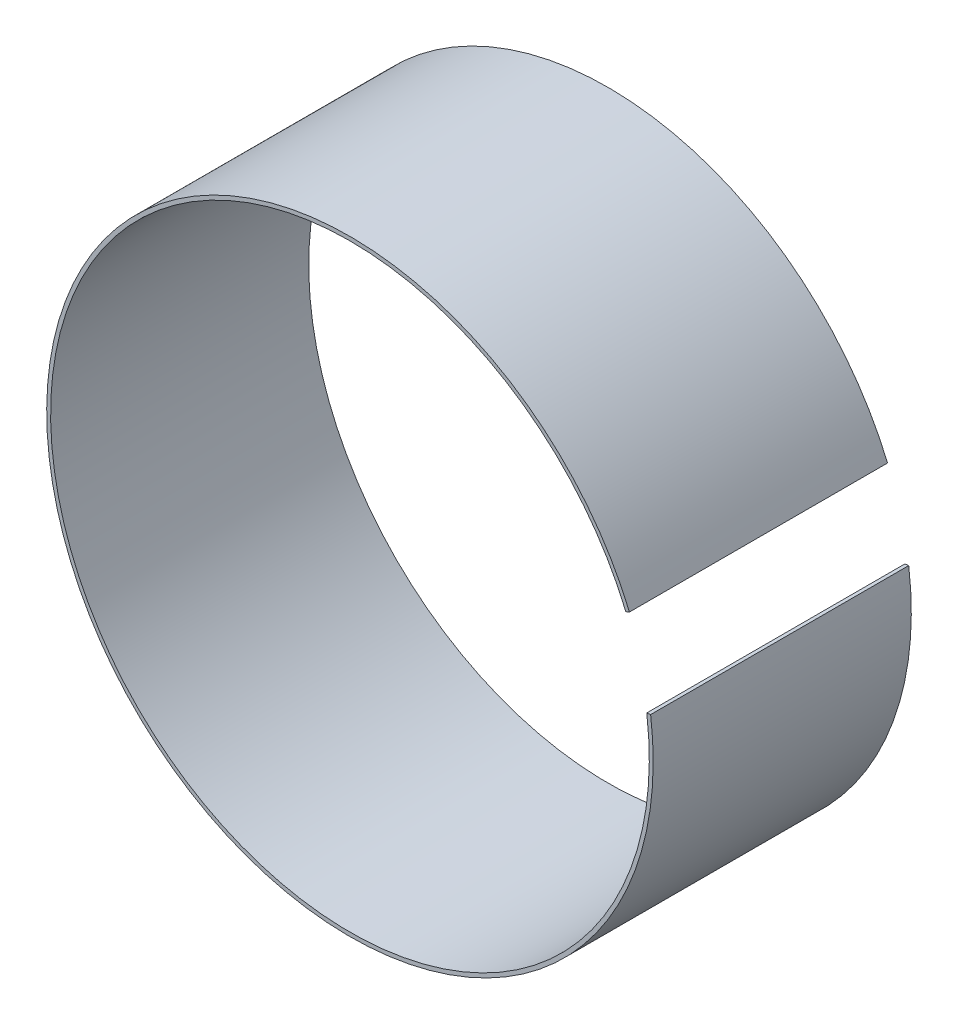
SolidWorks part; units mm, degrees
ref_plane "Front Plane" through (0, 0, 0) normal (0, 0, 1) x (1, 0, 0)
ref_plane "Top Plane" through (0, 0, 0) normal (0, 1, 0) x (1, 0, 0)
ref_plane "Right Plane" through (0, 0, 0) normal (1, 0, 0) x (0, 0, -1)
sketch "Sketch3" plane through (0, 0, 0) normal (0, 0, 1) x (1, 0, 0)
  arc A0 (38.444, 5.0451) -> (35.7365, 15.0451) centre (0, 0.0031) cw
  point P3 (0, 0)
  dimension "D1" = 10
extrude "Extrude-Thin5" add sketch "Sketch3" along normal blind 33 thin
